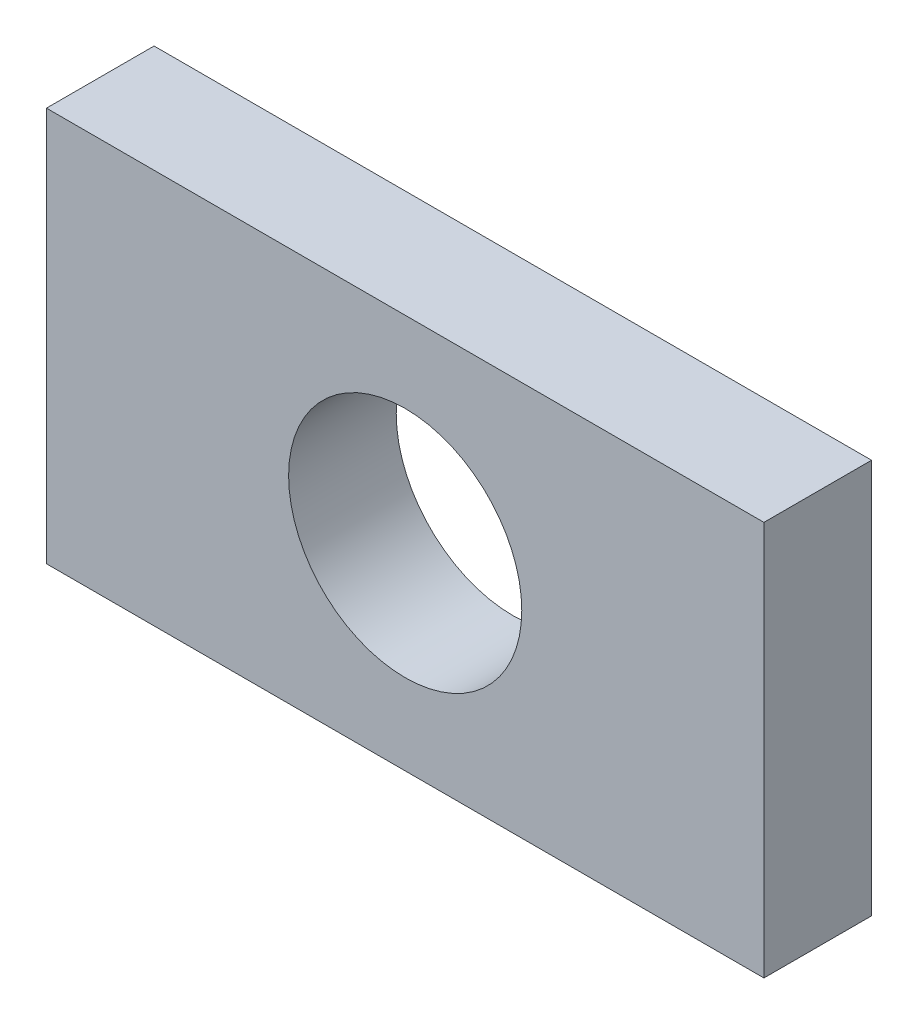
SolidWorks part; units mm, degrees
material "AISI 321 Отожженная нержавеющая сталь (SS)"
ref_plane "Спереди" through (0, 0, 0) normal (0, 0, 1) x (1, 0, 0)
ref_plane "Сверху" through (0, 0, 0) normal (0, 1, 0) x (1, 0, 0)
ref_plane "Справа" through (0, 0, 0) normal (1, 0, 0) x (0, 0, -1)
sketch "Эскиз1" plane through (0, 0, 0) normal (0, 0, 1) x (1, 0, 0)
  line L0 (0, 406) -> (0, 417) construction
  line L1 (-10, 417) -> (10, 417)
  line L2 (-10, 417) -> (-10, 406)
  line L3 (-10, 406) -> (10, 406)
  line L4 (10, 417) -> (10, 406)
  circle A0 centre (0, 411.5) radius 3.25
  dimension "D3" = 6.5
  dimension "D1" = 20
  dimension "D2" = 11
extrude "Бобышка-Вытянуть1" add sketch "Эскиз1" against normal blind 3
